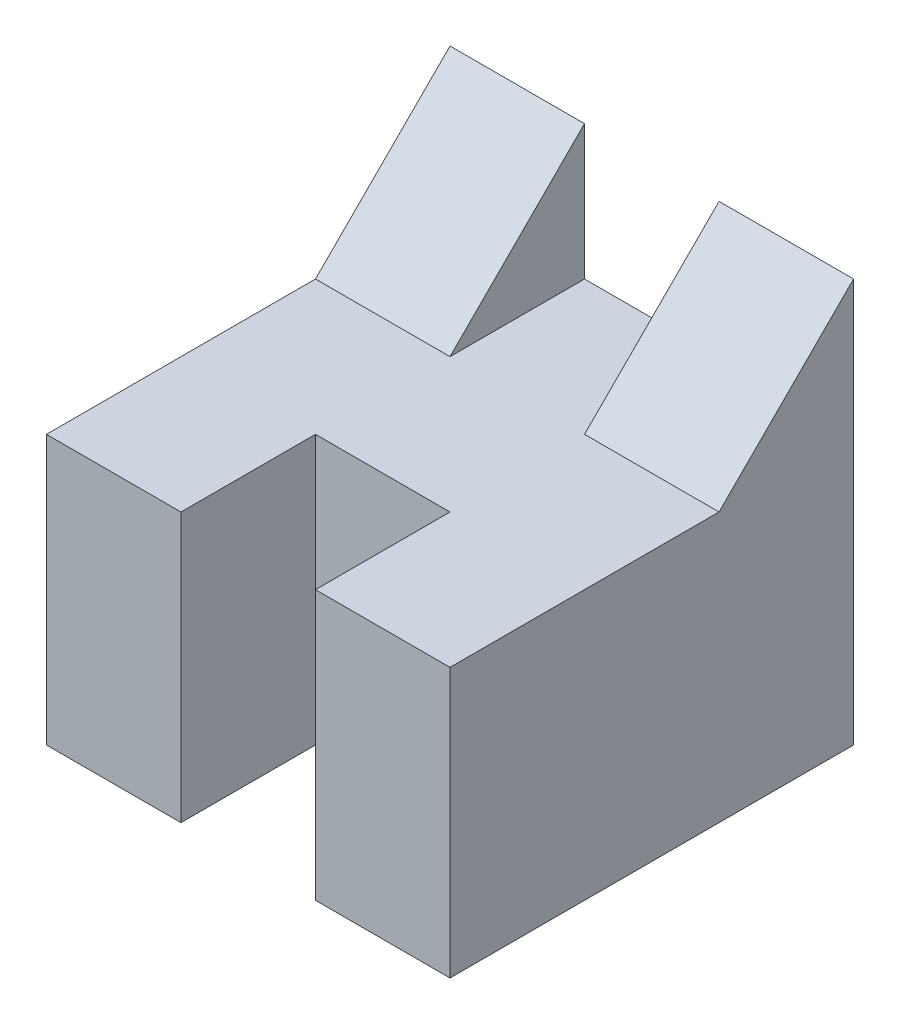
SolidWorks part; units mm, degrees
ref_plane "前基準面" through (0, 0, 0) normal (0, 0, 1) x (1, 0, 0)
ref_plane "上基準面" through (0, 0, 0) normal (0, 1, 0) x (1, 0, 0)
ref_plane "右基準面" through (0, 0, 0) normal (1, 0, 0) x (0, 0, -1)
sketch "草圖1" plane through (0, 0, 0) normal (0, 0, 1) x (1, 0, 0)
  line L1 (0, 0) -> (30, 0)
  line L2 (0, 0) -> (0, 30)
  line L3 (0, 30) -> (30, 30)
  line L4 (30, 0) -> (30, 30)
  dimension "D1" = 30
  dimension "D2" = 30
extrude "填料-伸1" add sketch "草圖1" against normal blind 30
sketch "草圖42" plane through (0, 0, 0) normal (0, 0, 1) x (1, 0, 0)
  line L0 (30, 30) -> (0, 30) construction
  line L1 (10, 30) -> (20, 30)
  line L2 (10, 30) -> (10, 20)
  line L3 (10, 20) -> (20, 20)
  line L4 (20, 30) -> (20, 20)
  line L5 (0, 30) -> (0, 0) construction
  dimension "D1" = 10
  dimension "D2" = 10
  dimension "D3" = 10
extrude "除料-伸長29" cut sketch "草圖42" against normal through all
sketch "草圖43" plane through (30, 0, 0) normal (1, 0, 0) x (0, 0, -1)
  line L0 (0, 16.5) -> (0, -16.5) construction
  line L1 (0, 30) -> (20, 30)
  line L2 (0, 30) -> (0, 20)
  line L3 (0, 20) -> (20, 20)
  line L4 (20, 30) -> (20, 20)
  line L5 (30, 30) -> (0, 30) construction
  line L6 (20, 20) -> (30, 30)
  line L7 (30, 30) -> (20, 30)
  line M4 (0, 30) -> (0, 0)
  line M7 (30, 30) -> (0, 30)
  dimension "D1" = 20
  dimension "D2" = 10
  dimension "D3" = 10
extrude "除料-伸長30" cut sketch "草圖43" against normal through all contours L4 L6 M7 | L4 L3 M7 M4
sketch "草圖44" plane through (0, 20, 0) normal (0, 1, 0) x (1, 0, 0)
  line L0 (-16.5, 0) -> (16.5, 0) construction
  line L1 (10, 0) -> (20, 0)
  line L2 (10, 0) -> (10, 10)
  line L3 (10, 10) -> (20, 10)
  line L4 (20, 0) -> (20, 10)
  line L5 (0, 0) -> (0, 20) construction
  dimension "D1" = 10
  dimension "D2" = 10
  dimension "D3" = 10
extrude "除料-伸長31" cut sketch "草圖44" against normal through all
